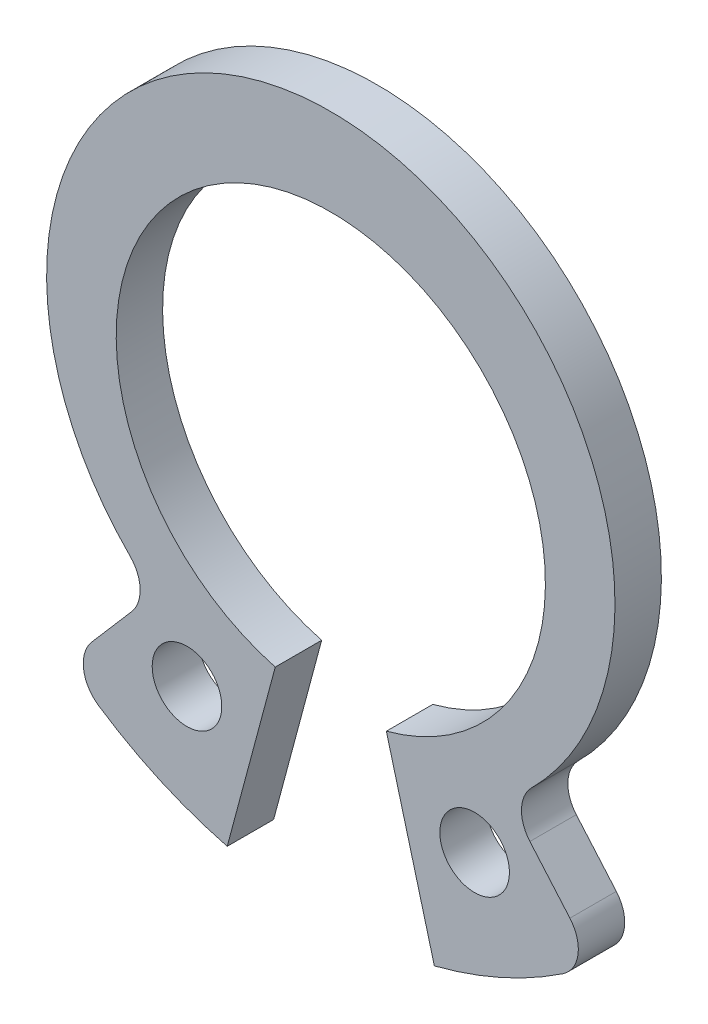
SolidWorks part; units mm, degrees
ref_plane "Plan1" through (0, 0, 0) normal (0, 0, 1) x (1, 0, 0)
ref_plane "Plan2" through (0, 0, 0) normal (0, 1, 0) x (1, 0, 0)
ref_plane "Plan3" through (0, 0, 0) normal (1, 0, 0) x (0, 0, -1)
sketch "Esquisse1" plane through (0, 0, 0) normal (0, 0, 1) x (1, 0, 0)
  line L0 (0, 0) -> (1.7859, -6.6649) construction
  line L1 (0, 0) -> (0, -67.082) construction
  line L2 (3.4326, -3.9828) -> (4.1225, -4.7834)
  line L3 (0.9576, -3.5739) -> (1.7859, -6.6649)
  line L4 (-0.9576, -3.5739) -> (-1.7859, -6.6649)
  line L5 (-3.4326, -3.9828) -> (-4.1225, -4.7834)
  line L6 (0.9576, -3.5739) -> (4.0019, -5.6736) construction
  line L7 (0, 0) -> (0, 3.7) construction
  line L8 (0, 3.7) -> (0, 5.2) construction
  arc A0 (0.9576, -3.5739) -> (-0.9576, -3.5739) centre (0, 0) ccw
  arc A1 (1.7859, -6.6649) -> (4.0019, -5.6736) centre (0, 0.3) ccw
  arc A2 (3.463, -3.1666) -> (-3.463, -3.1666) centre (0, 0.3) ccw
  arc A3 (-4.0019, -5.6736) -> (-1.7859, -6.6649) centre (0, 0.3) ccw
  arc A4 (-3.463, -3.1666) -> (-3.4326, -3.9828) centre (-3.8871, -3.5911) cw
  arc A5 (3.463, -3.1666) -> (3.4326, -3.9828) centre (3.8871, -3.5911) ccw
  circle A6 centre (2.4798, -4.6237) radius 0.6
  circle A7 centre (-2.4798, -4.6237) radius 0.6
  arc A8 (-4.0019, -5.6736) -> (-4.1225, -4.7834) centre (-3.668, -5.1751) cw
  arc A9 (4.0019, -5.6736) -> (4.1225, -4.7834) centre (3.668, -5.1751) ccw
  point P8 (0, 0)
  point P22 (-4.5439, -5.2724)
  dimension "D1" = 7.4
  dimension "D2" = 3.2
  dimension "D3" = 1.5
  dimension "R" = 0.6
  dimension "D8" = 1.2
  dimension "D4" = 0.3
  dimension "D5" = 3
  dimension "a" = 15
extrude "Base-Extrusion" add sketch "Esquisse1" along normal blind 0.8
equation "\"R@Esquisse1\" = \"D8@Esquisse1\"/2"
equation "\"D4@Esquisse1\"=\"R@Esquisse1\"/2"
equation "\"D5@Esquisse1\"=\"D8@Esquisse1\"*2.5"
